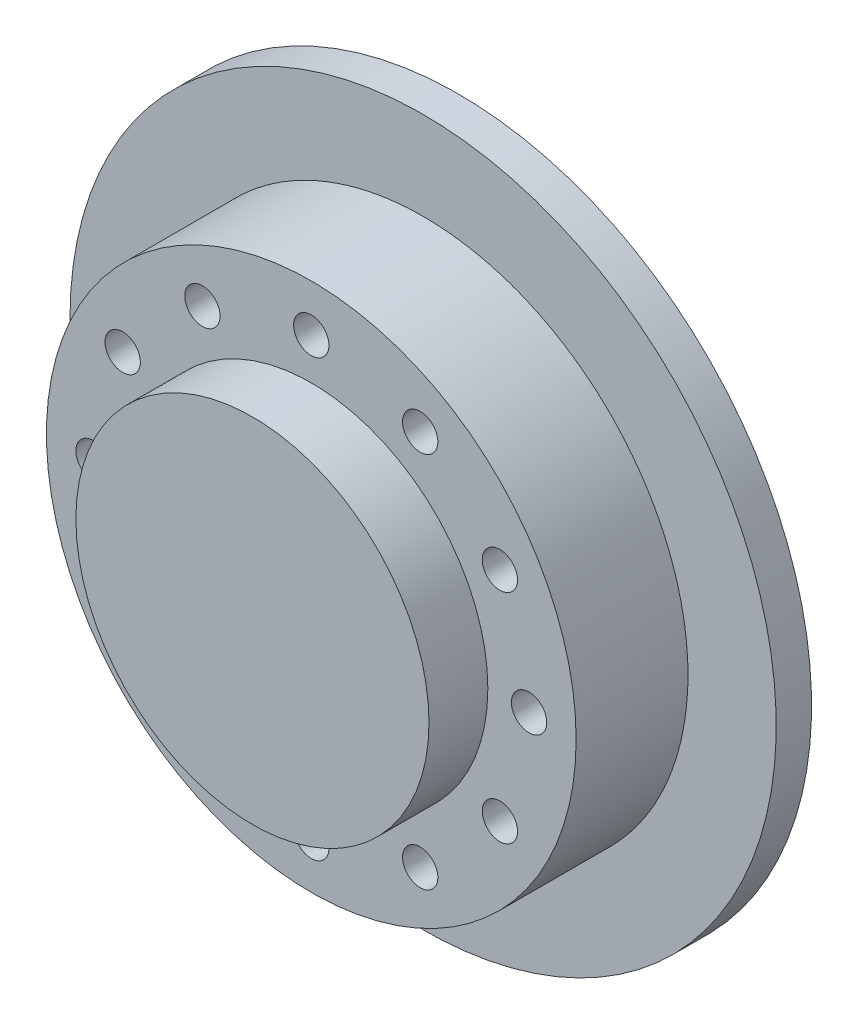
SolidWorks part; units mm, degrees
ref_plane "前视基准面" through (0, 0, 0) normal (0, 0, 1) x (1, 0, 0)
ref_plane "上视基准面" through (0, 0, 0) normal (0, 1, 0) x (1, 0, 0)
ref_plane "右视基准面" through (0, 0, 0) normal (1, 0, 0) x (0, 0, -1)
other "Configuration Table"
sketch "草图1" plane through (0, 0, 0) normal (0, 0, 1) x (1, 0, 0)
  circle A0 centre (0, 0) radius 22.5
  dimension "D1" = 45
extrude "凸台-拉伸1" add sketch "草图1" along normal blind 12.5
sketch "草图2" plane through (0, 0, 12.5) normal (0, 0, 1) x (1, 0, 0)
  circle A0 centre (0, 0) radius 15
  dimension "D1" = 30
extrude "凸台-拉伸2" add sketch "草图2" along normal blind 5
sketch "草图3" plane through (0, 0, 12.5) normal (0, 0, 1) x (1, 0, 0)
  circle A0 centre (0, 0) radius 18.5 construction
  circle A1 centre (0, 18.5) radius 1.5
  dimension "D1" = 37
  dimension "D2" = 3
extrude "切除-拉伸1" cut sketch "草图3" against normal blind 5
sketch "草图5" plane through (0, 0, 12.5) normal (0, 0, 1) x (1, 0, 0)
  circle A0 centre (0, 18.5) radius 1.5
  dimension "D1" = 3
extrude "切除-拉伸2" cut sketch "草图5" against normal through all
sketch "草图9" plane through (0, 0, 0) normal (0, 0, -1) x (-1, 0, 0)
  line L1 (1.2045, 21.4381) -> (-1.9422, 21.0122)
  line L2 (-1.9422, 21.0122) -> (-3.1467, 18.0741)
  line L3 (-3.1467, 18.0741) -> (-1.2045, 15.5619)
  line L4 (-1.2045, 15.5619) -> (1.9422, 15.9878)
  line L5 (1.9422, 15.9878) -> (3.1467, 18.9259)
  line L6 (3.1467, 18.9259) -> (1.2045, 21.4381)
  circle A0 centre (0, 18.5) radius 2.75 construction
  dimension "D1" = 5.5
extrude "切除-拉伸6" cut sketch "草图9" against normal blind 3
pattern_circular "阵列(圆周)1" count 12 over 360 about axis through (0, 0, 0) along (0, 0, 1) of "切除-拉伸1", "切除-拉伸6", "切除-拉伸2"
sketch "草图10" plane through (0, 0, 0) normal (0, 0, -1) x (-1, 0, 0)
  circle A0 centre (0, 0) radius 22.5
  circle A1 centre (0, 0) radius 30
  circle A2 centre (0, 0) radius 22.5 construction
  dimension "D1" = 60
extrude "凸台-拉伸3" add sketch "草图10" against normal blind 3 separate body
